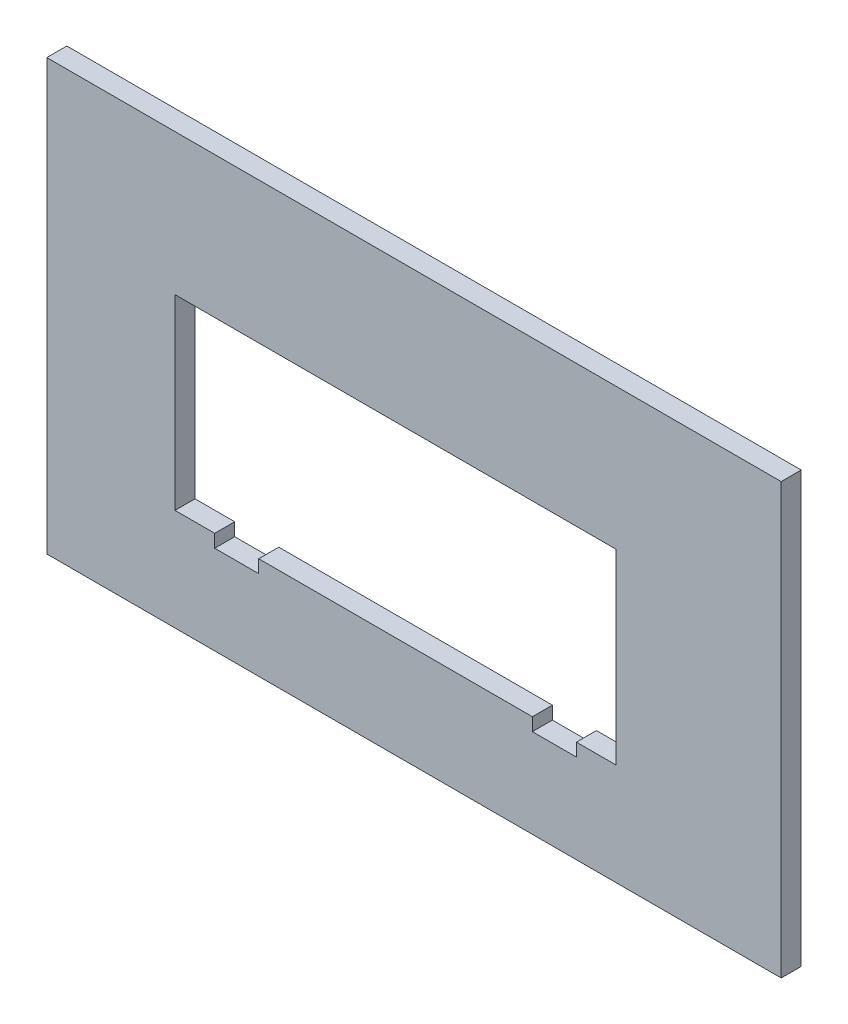
SolidWorks part; units mm, degrees
ref_plane "Front Plane" through (0, 0, 0) normal (0, 0, 1) x (1, 0, 0)
ref_plane "Top Plane" through (0, 0, 0) normal (0, 1, 0) x (1, 0, 0)
ref_plane "Right Plane" through (0, 0, 0) normal (1, 0, 0) x (0, 0, -1)
sketch "Sketch1" plane through (0, 0, 0) normal (0, 0, 1) x (1, 0, 0)
  line L0 (264.9058, 89.4547) -> (297.957, 89.4547) construction
  line L37 (274.4314, 75.4547) -> (288.4314, 75.4547)
  line L38 (274.4314, 80.1554) -> (274.4314, 75.4547)
  line L39 (272.9063, 80.1554) -> (274.4314, 80.1554)
  line L40 (272.9063, 75.6847) -> (272.9063, 80.1554)
  line L41 (271.1802, 75.6847) -> (272.9063, 75.6847)
  line L42 (271.1802, 74.4846) -> (271.1802, 75.6847)
  line L43 (267.88, 75.6847) -> (267.88, 74.4846)
  line L44 (267.88, 74.4846) -> (271.1802, 74.4846)
  line L45 (266.1559, 75.6847) -> (267.88, 75.6847)
  line L46 (266.1559, 81.9554) -> (266.1559, 75.6847)
  line L47 (265.3309, 81.9554) -> (266.1559, 81.9554)
  line L48 (265.3309, 84.7556) -> (265.3309, 81.9554)
  line L49 (266.1559, 84.7556) -> (265.3309, 84.7556)
  line L50 (266.1559, 87.9858) -> (266.1559, 84.7556)
  line L51 (274.4314, 84.7556) -> (272.9063, 84.7556)
  line L52 (272.9063, 84.7556) -> (272.9063, 87.9858)
  line L53 (274.4314, 89.4547) -> (274.4314, 84.7556)
  line L54 (288.4314, 89.4547) -> (274.4314, 89.4547)
  line L55 (288.4314, 84.7554) -> (288.4314, 89.4547)
  line L56 (296.7069, 75.6847) -> (296.7069, 81.9554)
  line L57 (296.7069, 81.9554) -> (297.531, 81.9554)
  line L58 (297.531, 81.9554) -> (297.531, 84.7554)
  line L59 (297.531, 84.7554) -> (296.7069, 84.7554)
  line L60 (296.7069, 84.7554) -> (296.7069, 87.9856)
  line L61 (296.7069, 87.9856) -> (289.9565, 87.9856)
  line L62 (289.9565, 87.9856) -> (289.9565, 84.7554)
  line L63 (289.9565, 84.7554) -> (288.4314, 84.7554)
  line L64 (288.4314, 75.4547) -> (288.4314, 80.1554)
  line L65 (288.4314, 80.1554) -> (289.9565, 80.1554)
  line L66 (289.9565, 80.1554) -> (289.9565, 75.6847)
  line L67 (289.9565, 75.6847) -> (291.6806, 75.6847)
  line L68 (291.6806, 75.6847) -> (291.6806, 74.4846)
  line L69 (291.6806, 74.4846) -> (294.9808, 74.4846)
  line L70 (294.9808, 74.4846) -> (294.9808, 75.6847)
  line L71 (294.9808, 75.6847) -> (296.7069, 75.6847)
  line L72 (272.9063, 87.9858) -> (266.1559, 87.9858)
  line L73 (288.4314, 89.4547) -> (274.4314, 89.4547)
  point P11 (281.4314, 89.4547)
  dimension "D1" = 14
sketch "Sketch3" plane through (0, 0, 0) normal (0, 0, 1) x (1, 0, 0)
  line L1 (255.2994, 100.0325) -> (310.3234, 100.0325)
  line L2 (255.2994, 100.0325) -> (255.2994, 67.8221)
  line L3 (255.2994, 67.8221) -> (310.3234, 67.8221)
  line L4 (310.3234, 100.0325) -> (310.3234, 67.8221)
extrude "Boss-Extrude1" add sketch "Sketch3" along normal blind 1.5
sketch "Sketch4" plane through (0, 0, 1.5) normal (0, 0, 1) x (1, 0, 0)
  line L1 (264.9058, 89.4547) -> (297.957, 89.4547)
  line L2 (264.9058, 89.4547) -> (264.9058, 75.4547)
  line L3 (264.9058, 75.4547) -> (297.957, 75.4547)
  line L4 (297.957, 89.4547) -> (297.957, 75.4547)
  line L5 (278.9058, 89.4547) -> (283.957, 89.4547)
  line L6 (278.9058, 89.4547) -> (278.9058, 75.4547)
  line L7 (278.9058, 75.4547) -> (283.957, 75.4547)
  line L8 (283.957, 89.4547) -> (283.957, 75.4547)
  dimension "D1" = 14
  dimension "D2" = 14
  dimension "D3" = 14
extrude "Cut-Extrude1" cut sketch "Sketch4" against normal blind 1.5 contours L6 L1 L2 L3 | L1 L8 L3 L4
extrude "Cut-Extrude4" cut sketch "Sketch1" against normal through all and the other way through all contours L52 L72 L50 L49 L48 L47 L46 L45 L43 L44 L42 L41 L40 L39 L38 L37 L64 L65 L66 L67 L68 L69 L70 L71 L56 L57 L58 L59 L60 L61 L62 L63 L55 L54 L53 L51
